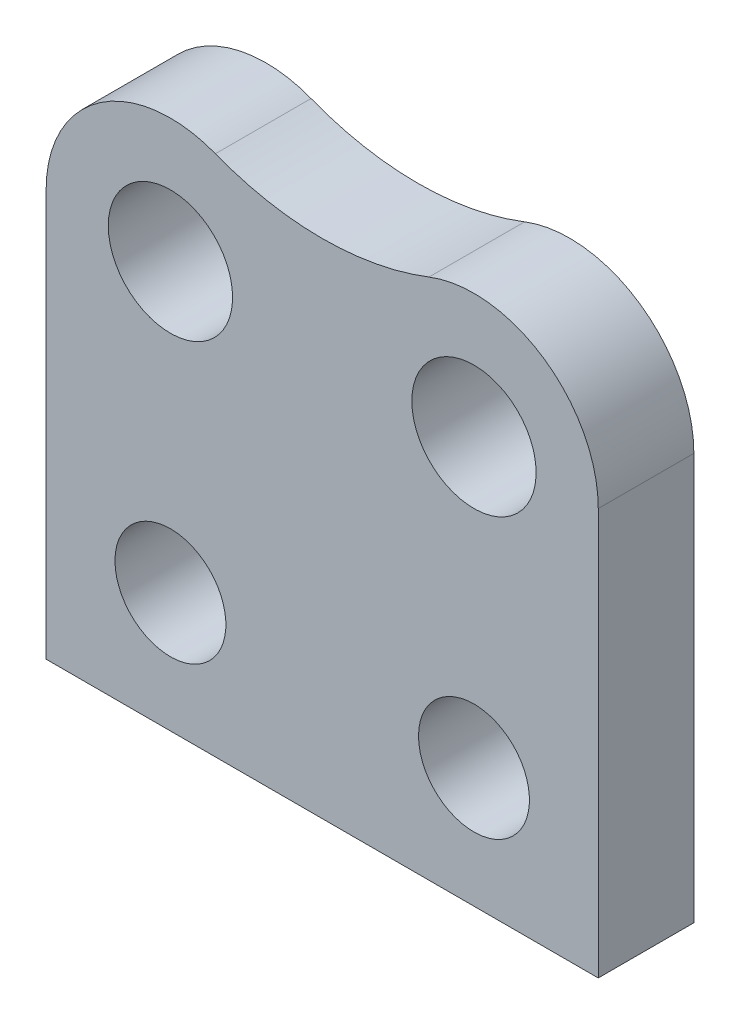
SolidWorks part; units mm, degrees
ref_plane "Front Plane" through (0, 0, 0) normal (0, 0, 1) x (1, 0, 0)
ref_plane "Top Plane" through (0, 0, 0) normal (0, 1, 0) x (1, 0, 0)
ref_plane "Right Plane" through (0, 0, 0) normal (1, 0, 0) x (0, 0, -1)
sketch "Sketch1" plane through (0, 0, 0) normal (0, 0, 1) x (1, 0, 0)
  line L0 (0, 0) -> (0, 10)
  line L1 (0, 10) -> (7.5, 10)
  line L2 (7.5, 10) -> (12.4992, 14.9992)
  line L3 (12.4992, 14.9992) -> (12.4992, 34.4)
  line L4 (12.4992, 34.4) -> (24.7492, 34.4)
  line L5 (24.7492, 34.4) -> (24.7492, 14.9992)
  line L6 (24.7492, 14.9992) -> (29.7485, 10)
  line L7 (29.7485, 10) -> (37.2485, 10)
  line L8 (37.2485, 10) -> (37.2485, 0)
  line L9 (37.2485, 0) -> (0, 0)
  dimension "D1" = 7.07
  dimension "D2" = 7.07
  dimension "D3" = 34.4
  dimension "D4" = 10
  dimension "D5" = 10
  dimension "D6" = 7.5
  dimension "D7" = 7.5
  dimension "D8" = 12.25
  dimension "D9" = 37.2485
extrude "Boss-Extrude1" add sketch "Sketch1" along normal blind 6.18
sketch "Sketch2" plane through (0, 10, 0) normal (0, 1, 0) x (1, 0, 0)
  line L2 (7.5, 0) -> (0, 0) construction
  line L5 (7.5, -6.18) -> (7.5, 0) construction
  line L6 (37.2485, 0) -> (29.7485, 0) construction
  line L7 (37.2485, -6.18) -> (37.2485, 0) construction
  circle A0 centre (3.75, -3.09) radius 2.1
  circle A1 centre (33.4985, -3.09) radius 2.1
  dimension "D1" = 4.2
  dimension "D2" = 3.09
  dimension "D3" = 3.75
  dimension "D4" = 3.09
  dimension "D5" = 3.75
extrude "Cut-Extrude1" cut sketch "Sketch2" against normal through all
fillet "Fillet1" radius 2 6 edges at (0, 5, 0) (0, 5, 6.18) (37.2485, 5, 0) (37.2485, 5, 6.18) (24.7492, 34.4, 3.09) (12.4992, 34.4, 3.09)
sketch "Sketch3" plane through (0, 0, 0) normal (0, 0, -1) x (-1, 0, 0)
  line L1 (-21.1131, 29.9595) -> (-9.5631, 29.9595)
  line L2 (-21.1131, 29.9595) -> (-21.1131, 21.4548)
  line L3 (-21.1131, 21.4548) -> (-9.5631, 21.4548)
  line L4 (-9.5631, 29.9595) -> (-9.5631, 21.4548)
  circle A1 centre (-18.5131, 23.9595) radius 1.16
  circle A2 centre (-12.1631, 23.9595) radius 1.16
  circle A4 centre (-18.5131, 29.9595) radius 1.155
  circle A5 centre (-12.1631, 29.9595) radius 1.155
  circle A6 centre (-18.5131, 29.9595) radius 2.6
  circle A7 centre (-12.1631, 29.9595) radius 2.6
  circle A8 centre (-15.3381, 38.1346) radius 6.17
  line M34 (-12.4992, 14.9992) -> (-12.4992, 32.4)
  arc M35 (-12.4992, 32.4) -> (-14.4992, 34.4) centre (-14.4992, 32.4) ccw
  dimension "D1" = 2.32
  dimension "D2" = 6
  dimension "D3" = 6
extrude "Boss-Extrude2" add sketch "Sketch3" along normal blind 2 contours A7 L1 A6 L2 L3 A2 A1 M34 | A7 A2 L3 L4 M34 | L1 A7 A5 M34 | A7 L1 A5 M34 | L1 A7 A5 M35 M34 | A7 L1 A5 M35 M34 | L1 A6 A4 | L1 A6 A4 | A8 A6 L1 A7
sketch "Sketch5" plane through (0, 0, 6.18) normal (0, 0, 1) x (1, 0, 0)
  line L1 (-4.9802, 37.9454) -> (41.2524, 37.9454)
  line L2 (-4.9802, 37.9454) -> (-4.9802, -3.7546)
  line L3 (-4.9802, -3.7546) -> (41.2524, -3.7546)
  line L4 (41.2524, 37.9454) -> (41.2524, -3.7546)
extrude "Cut-Extrude2" cut sketch "Sketch5" against normal blind 6.18
sketch "Sketch9" plane through (0, 0, -2) normal (0, 0, -1) x (-1, 0, 0)
  circle A0 centre (-18.5131, 29.9595) radius 1.3
  circle A1 centre (-12.1631, 29.9595) radius 1.3
  dimension "D1" = 2.6
extrude "Cut-Extrude3" cut sketch "Sketch9" against normal through all
